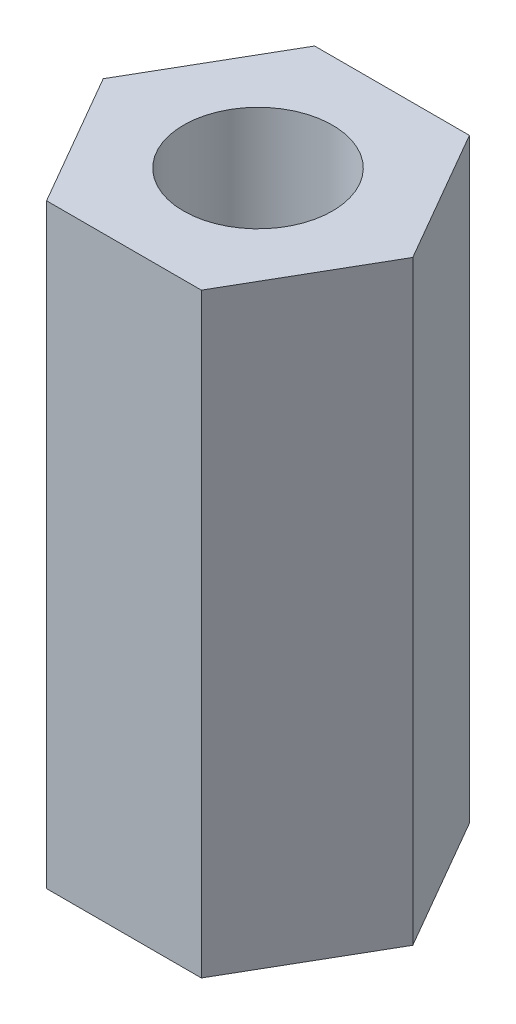
SolidWorks part; units mm, degrees
material "尼龙 101"
ref_plane "前视基准面" through (0, 0, 0) normal (0, 0, 1) x (1, 0, 0)
ref_plane "上视基准面" through (0, 0, 0) normal (0, 1, 0) x (1, 0, 0)
ref_plane "右视基准面" through (0, 0, 0) normal (1, 0, 0) x (0, 0, -1)
sketch "草图1" plane through (0, 0, 0) normal (0, 1, 0) x (1, 0, 0)
  line L1 (1.299, -2.25) -> (2.5981, 0)
  line L2 (2.5981, 0) -> (1.299, 2.25)
  line L3 (1.299, 2.25) -> (-1.299, 2.25)
  line L4 (-1.299, 2.25) -> (-2.5981, 0)
  line L5 (-2.5981, 0) -> (-1.299, -2.25)
  line L6 (-1.299, -2.25) -> (1.299, -2.25)
  circle A0 centre (0, 0) radius 2.25 construction
  circle A1 centre (0, 0) radius 1.25
  dimension "D2" = 2.5
  dimension "D1" = 4.5
extrude "凸台-拉伸1" add sketch "草图1" along normal blind 10
